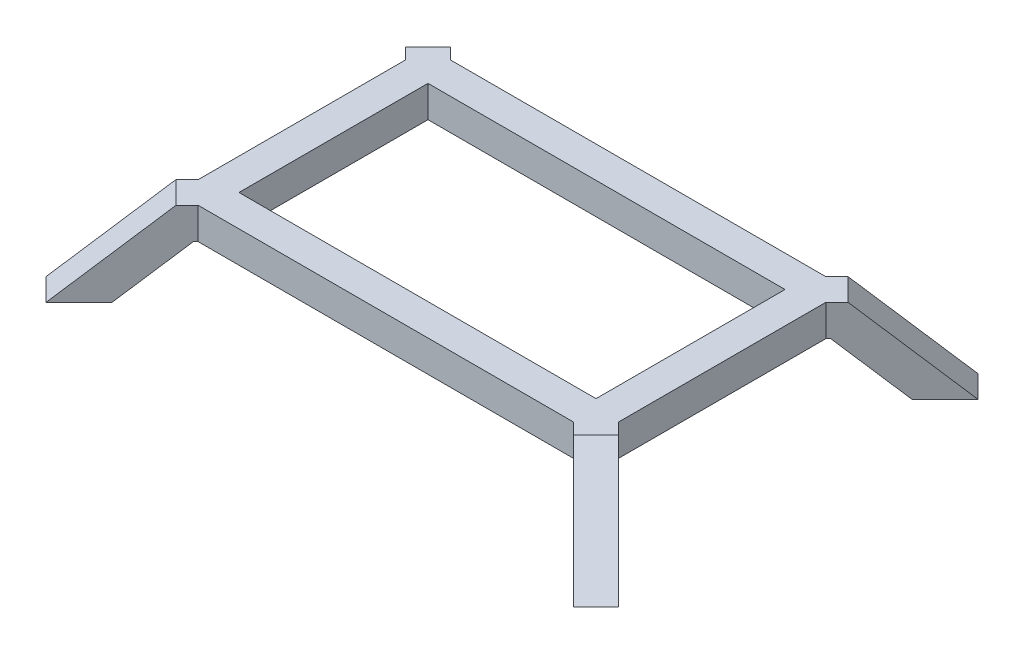
SolidWorks part; units mm, degrees
ref_plane "Front Plane" through (0, 0, 0) normal (0, 0, 1) x (1, 0, 0)
ref_plane "Top Plane" through (0, 0, 0) normal (0, 1, 0) x (1, 0, 0)
ref_plane "Right Plane" through (0, 0, 0) normal (1, 0, 0) x (0, 0, -1)
sketch "Sketch1" plane through (0, 0, 0) normal (0, 1, 0) x (1, 0, 0)
  line L0 (-215.9, -114.3) -> (-215.9, 114.3)
  line L1 (-254, -152.4) -> (254, -152.4)
  line L2 (-254, -152.4) -> (-254, 152.4)
  line L3 (-254, 152.4) -> (254, 152.4)
  line L4 (254, -152.4) -> (254, 152.4)
  line L5 (-254, -152.4) -> (254, 152.4) construction
  line L6 (-254, 152.4) -> (254, -152.4) construction
  line L7 (-215.9, 114.3) -> (215.9, 114.3)
  line L8 (215.9, -114.3) -> (215.9, 114.3)
  line L9 (-215.9, -114.3) -> (215.9, -114.3)
  point P0 (0, 0)
  dimension "D1" = 304.8
  dimension "D2" = 508
  dimension "D3" = 38.1
extrude "Boss-Extrude1" add sketch "Sketch1" along normal blind 38.1
ref_plane "Plane1" through (-50.8, 0, -50.8) normal (0.7071, 0, 0.7071) x (0.7071, 0, -0.7071)
sketch "Sketch3" plane through (-50.8, 0, -50.8) normal (0.7071, 0, 0.7071) x (0.7071, 0, -0.7071)
  line L0 (-287.3682, 38.1) -> (-398.4889, -63.5)
  line L1 (-398.4889, -63.5) -> (-342.0263, -63.5)
  line L2 (-342.0263, -63.5) -> (-272.5759, 0)
  line L3 (-398.4889, -63.5) -> (0, -63.5) construction
  line L4 (0, -63.5) -> (0, 0) construction
  line L5 (-287.3682, 38.1) -> (-266.9427, 38.1)
  line L6 (-287.3682, 38.1) -> (71.842, 38.1) construction
  line L7 (-266.9427, 38.1) -> (-266.9427, 0)
  line L8 (-287.3682, 0) -> (71.842, 0) construction
  line L9 (-272.5759, 0) -> (-266.9427, 0)
  dimension "D1" = 63.5
  dimension "D2" = 38.1
extrude "Boss-Extrude3" add sketch "Sketch3" along normal mid plane 38.1
mirror "Mirror2" about plane through (0, 0, 0) normal (1, 0, 0) of "Boss-Extrude3"
mirror "Mirror3" about plane through (0, 0, 0) normal (0, 0, 1) of "Mirror2", "Boss-Extrude3"
